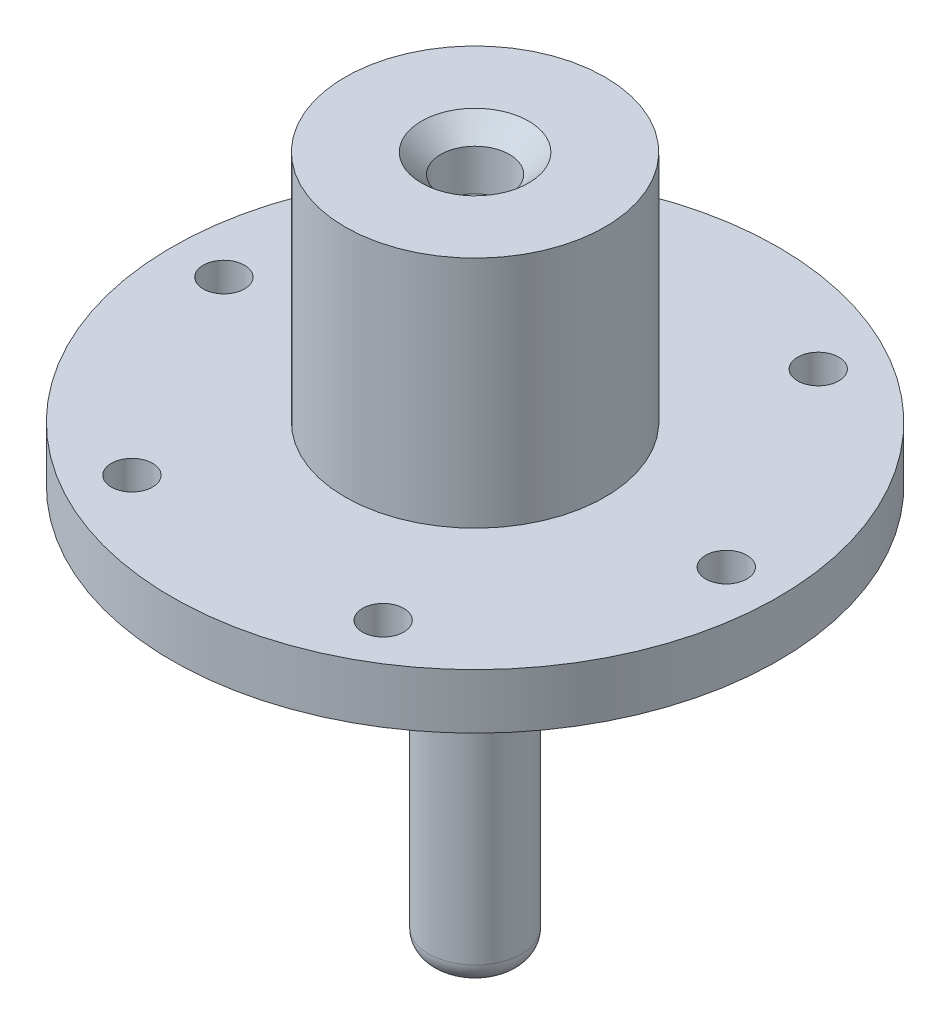
SolidWorks part; units mm, degrees
ref_plane "Front Plane" through (0, 0, 0) normal (0, 0, 1) x (1, 0, 0)
ref_plane "Top Plane" through (0, 0, 0) normal (0, 1, 0) x (1, 0, 0)
ref_plane "Right Plane" through (0, 0, 0) normal (1, 0, 0) x (0, 0, -1)
sketch "Sketch1" plane through (0, 0, 0) normal (0, 0, 1) x (1, 0, 0)
  line L0 (0, 0) -> (-15, 0)
  line L1 (-15, 0) -> (-15, -27)
  line L2 (-15, -27) -> (-35, -27)
  line L3 (-35, -27) -> (-35, -33.35)
  line L4 (-35, -33.35) -> (-12.5, -33.35)
  line L5 (-10, -35.85) -> (-10, -45.35)
  line L6 (-10, -45.35) -> (-5.3467, -50.0033)
  line L7 (-5.3467, -50.0033) -> (-5.3467, -77.5033)
  line L8 (-2.8467, -80.0033) -> (0, -80.0033)
  line L9 (0, -80.0033) -> (0, 0)
  line L10 (-12.5, -33.35) -> (-10, -35.85)
  arc A0 (-5.3467, -77.5033) -> (-2.8467, -80.0033) centre (-2.8467, -77.5033) ccw
  point P7 (-10, -33.35)
  point P15 (-5.3467, -80.0033)
  dimension "D9" = 2.5
  dimension "D1" = 5.3467
  dimension "D2" = 10
  dimension "D3" = 30
  dimension "D4" = 45
  dimension "D5" = 6.35
  dimension "D6" = 12
  dimension "D7" = 15
  dimension "D8" = 25
  dimension "D10" = 27
revolve "Revolve1" add sketch "Sketch1" angle 360 about L9
hole_wizard "1/16 NPT Tapped Hole1" positions "Sketch2" profile "Sketch4" size "1/16" standard "ANSI Inch"
sketch "Sketch2" plane through (0, 0, 0) normal (0, 1, 0) x (1, 0, 0)
  point P0 (0, 0)
sketch "Sketch4" plane through (0, 0, 0) normal (1, 0, 0) x (0, 0, 1)
  line L0 (0, 0) -> (0, 78.8467)
  line L1 (3.0734, 77) -> (0, 78.8467)
  line L2 (-3.0734, 77) -> (0, 78.8467) construction
  line L3 (3.0734, 77) -> (3.0734, 6.89)
  line L4 (3.0734, 6.89) -> (3.8291, 6.89)
  line L5 (3.8291, 6.89) -> (3.9689, 2.2224)
  line L6 (3.9689, 2.2224) -> (6.1913, 0)
  line L7 (6.1913, 0) -> (0, 0)
  line L8 (0, -6.35) -> (0, 107.95) construction
  line L9 (-3.9689, 2.2224) -> (-6.1913, 0) construction
  line L11 (-3.0734, 6.89) -> (-3.8291, 6.89) construction
  line L12 (-3.8291, 6.89) -> (-3.9689, 2.2224) construction
  dimension "Tap Drill Dia." = 6.1468
  dimension "Tap Drill Depth" = 77
  dimension "Thread Dia." = 7.9378
  dimension "Thread Angle" = 3.43
  dimension "Thread Depth" = 6.89
  dimension "C'Sink Dia." = 12.3825
  dimension "C'Sink Angle" = 90
  dimension "Drill Angle" = 118
sketch "Sketch5" plane through (0, -33.35, 0) normal (0, -1, 0) x (-1, 0, 0)
  circle A0 centre (0, 0) radius 21
  circle A1 centre (0, 0) radius 24
  dimension "D1" = 42
  dimension "D2" = 48
extrude "Cut-Extrude1" cut sketch "Sketch5" against normal blind 3
hole_wizard "3/16 (0.1875) Diameter Hole1" positions "Sketch6" profile "Sketch8" hole size "3/16" standard "ANSI Inch" end condition through all
sketch "Sketch6" plane through (0, -27, 0) normal (0, 1, 0) x (1, 0, 0)
  point P0 (29, 0)
  dimension "D1" = 29
sketch "Sketch8" plane through (29, -27, 0) normal (1, 0, 0) x (0, 0, 1)
  line L0 (0, 0) -> (0, 53.0033)
  line L1 (0, 53.0033) -> (2.3812, 53.0033)
  line L2 (2.3812, 53.0033) -> (2.3812, 0)
  line L5 (2.3812, 0) -> (0, 0)
  line L11 (0, -6.35) -> (0, 107.95) construction
  dimension "Thru Hole Dia." = 4.7625
  dimension "Thru Hole Depth" = 53.0033
pattern_circular "CirPattern1" count 6 over 360 about axis through (0, 0, 0) along (0, 1, 0) of "3/16 (0.1875) Diameter Hole1"
